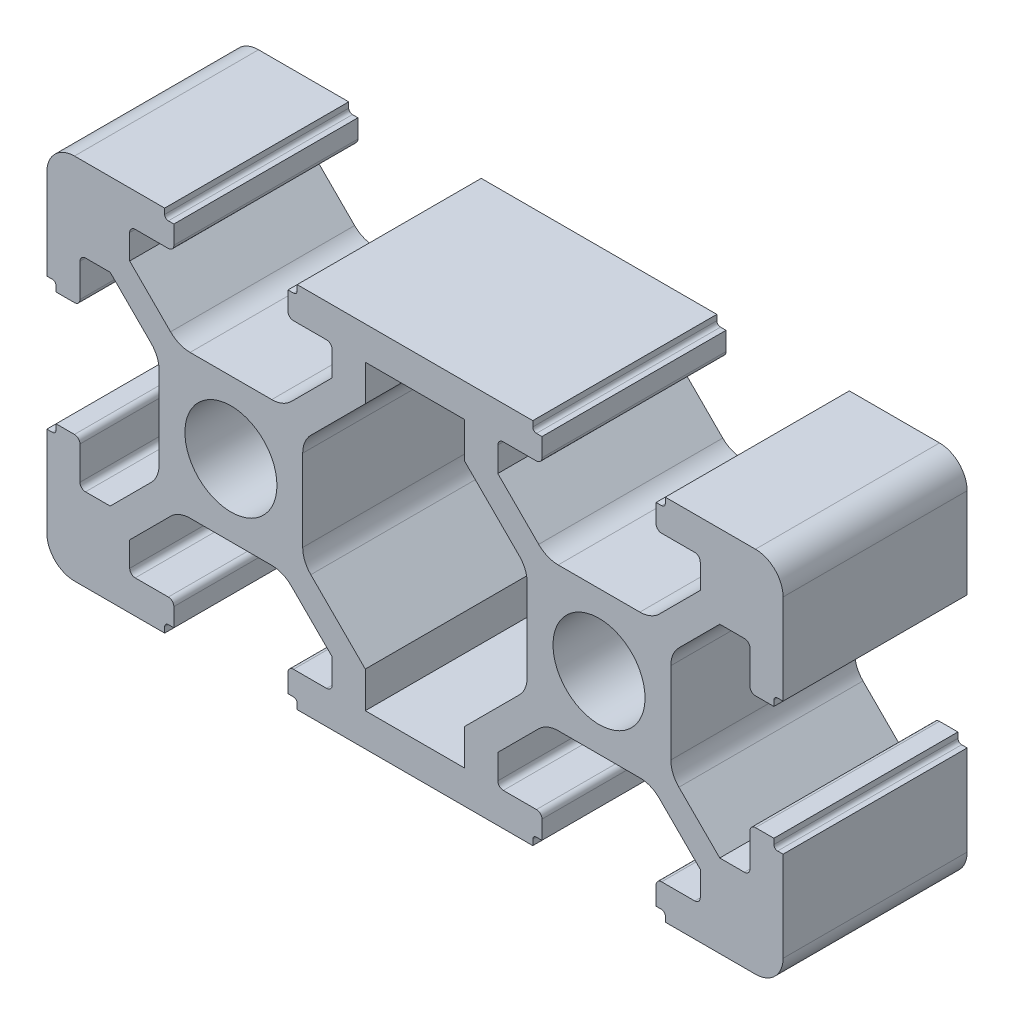
SolidWorks part; units mm, degrees
ref_plane "前视基准面" through (0, 0, 0) normal (0, 0, 1) x (1, 0, 0)
ref_plane "上视基准面" through (0, 0, 0) normal (0, 1, 0) x (1, 0, 0)
ref_plane "右视基准面" through (0, 0, 0) normal (1, 0, 0) x (0, 0, -1)
sketch "草图1" plane through (0, 0, 0) normal (0, 0, 1) x (1, 0, 0)
  line L0 (-1.9716, -6.6942) -> (-4.9322, -3.7335)
  line L1 (-5.3716, -2.6729) -> (-5.3716, 1.7645)
  line L2 (-4.9322, 2.8251) -> (-1.9716, 5.7858)
  line L3 (-0.7716, 9.5458) -> (-5.6716, 9.5458)
  line L4 (-5.6716, 9.5458) -> (-5.6716, 9.2458)
  line L5 (-5.8716, 9.0458) -> (-6.1716, 9.0458)
  line L6 (-6.1716, 9.0458) -> (-6.1716, 8.0458)
  line L7 (-5.8716, 7.7458) -> (-4.0716, 7.7458)
  line L8 (-3.7716, 7.4458) -> (-3.7716, 6.1058)
  line L9 (-3.7716, 6.1058) -> (-5.9922, 3.8851)
  line L10 (-7.0529, 3.4458) -> (-11.4903, 3.4458)
  line L11 (-12.5509, 3.8851) -> (-14.7716, 6.1058)
  line L12 (-14.7716, 6.1058) -> (-14.7716, 7.4458)
  line L13 (-14.4716, 7.7458) -> (-12.6716, 7.7458)
  line L14 (-12.3716, 8.0458) -> (-12.3716, 9.0458)
  line L15 (-12.3716, 9.0458) -> (-12.6716, 9.0458)
  line L16 (-12.8716, 9.2458) -> (-12.8716, 9.5458)
  line L17 (-12.8716, 9.5458) -> (-17.7716, 9.5458)
  line L18 (-19.2716, 8.0458) -> (-19.2716, 3.1458)
  line L19 (-19.2716, 3.1458) -> (-18.9716, 3.1458)
  line L20 (-18.7716, 2.9458) -> (-18.7716, 2.6458)
  line L21 (-18.7716, 2.6458) -> (-17.7716, 2.6458)
  line L22 (-17.4716, 2.9458) -> (-17.4716, 4.7458)
  line L23 (-17.1716, 5.0458) -> (-15.8316, 5.0458)
  line L24 (-15.8316, 5.0458) -> (-13.6109, 2.8251)
  line L25 (-13.1716, 1.7645) -> (-13.1716, -2.6729)
  line L26 (-13.6109, -3.7335) -> (-15.8316, -5.9542)
  line L27 (-15.8316, -5.9542) -> (-17.1716, -5.9542)
  line L28 (-17.4716, -5.6542) -> (-17.4716, -3.8542)
  line L29 (-17.7716, -3.5542) -> (-18.7716, -3.5542)
  line L30 (-18.7716, -3.5542) -> (-18.7716, -3.8542)
  line L31 (-18.9716, -4.0542) -> (-19.2716, -4.0542)
  line L32 (-19.2716, -4.0542) -> (-19.2716, -8.9542)
  line L33 (-17.7716, -10.4542) -> (-12.8716, -10.4542)
  line L34 (-12.8716, -10.4542) -> (-12.8716, -10.1542)
  line L35 (-12.6716, -9.9542) -> (-12.3716, -9.9542)
  line L36 (-12.3716, -9.9542) -> (-12.3716, -8.9542)
  line L37 (-12.6716, -8.6542) -> (-14.4716, -8.6542)
  line L38 (-14.7716, -8.3542) -> (-14.7716, -7.0142)
  line L39 (-14.7716, -7.0142) -> (-12.5509, -4.7935)
  line L40 (-11.4903, -4.3542) -> (-7.0529, -4.3542)
  line L41 (-5.9922, -4.7935) -> (-3.7716, -7.0142)
  line L42 (-3.7716, -7.0142) -> (-3.7716, -8.3542)
  line L43 (-4.0716, -8.6542) -> (-5.8716, -8.6542)
  line L44 (-6.1716, -8.9542) -> (-6.1716, -9.9542)
  line L45 (-6.1716, -9.9542) -> (-5.8716, -9.9542)
  line L46 (-5.6716, -10.1542) -> (-5.6716, -10.4542)
  line L47 (-5.6716, -10.4542) -> (-0.7716, -10.4542)
  line L48 (-0.7716, -10.4542) -> (7.1284, -10.4542)
  line L49 (7.1284, -10.4542) -> (7.1284, -10.1542)
  line L50 (7.3284, -9.9542) -> (7.6284, -9.9542)
  line L51 (7.6284, -9.9542) -> (7.6284, -8.9542)
  line L52 (7.3284, -8.6542) -> (5.5284, -8.6542)
  line L53 (5.2284, -8.3542) -> (5.2284, -7.0142)
  line L54 (5.2284, -7.0142) -> (7.4491, -4.7935)
  line L55 (8.5097, -4.3542) -> (12.9471, -4.3542)
  line L56 (14.0078, -4.7935) -> (16.2284, -7.0142)
  line L57 (16.2284, -7.0142) -> (16.2284, -8.3542)
  line L58 (15.9284, -8.6542) -> (14.1284, -8.6542)
  line L59 (13.8284, -8.9542) -> (13.8284, -9.9542)
  line L60 (13.8284, -9.9542) -> (14.1284, -9.9542)
  line L61 (14.3284, -10.1542) -> (14.3284, -10.4542)
  line L62 (14.3284, -10.4542) -> (19.2284, -10.4542)
  line L63 (20.7284, -8.9542) -> (20.7284, -4.0542)
  line L64 (20.7284, -4.0542) -> (20.4284, -4.0542)
  line L65 (20.2284, -3.8542) -> (20.2284, -3.5542)
  line L66 (20.2284, -3.5542) -> (19.2284, -3.5542)
  line L67 (18.9284, -3.8542) -> (18.9284, -5.6542)
  line L68 (18.6284, -5.9542) -> (17.2884, -5.9542)
  line L69 (17.2884, -5.9542) -> (15.0678, -3.7335)
  line L70 (14.6284, -2.6729) -> (14.6284, 1.7645)
  line L71 (15.0678, 2.8251) -> (17.2884, 5.0458)
  line L72 (17.2884, 5.0458) -> (18.6284, 5.0458)
  line L73 (18.9284, 4.7458) -> (18.9284, 2.9458)
  line L74 (19.2284, 2.6458) -> (20.2284, 2.6458)
  line L75 (20.2284, 2.6458) -> (20.2284, 2.9458)
  line L76 (20.4284, 3.1458) -> (20.7284, 3.1458)
  line L77 (20.7284, 3.1458) -> (20.7284, 8.0458)
  line L78 (19.2284, 9.5458) -> (14.3284, 9.5458)
  line L79 (14.3284, 9.5458) -> (14.3284, 9.2458)
  line L80 (14.1284, 9.0458) -> (13.8284, 9.0458)
  line L81 (13.8284, 9.0458) -> (13.8284, 8.0458)
  line L82 (14.1284, 7.7458) -> (15.9284, 7.7458)
  line L83 (16.2284, 7.4458) -> (16.2284, 6.1058)
  line L84 (16.2284, 6.1058) -> (14.0078, 3.8851)
  line L85 (12.9471, 3.4458) -> (8.5097, 3.4458)
  line L86 (7.4491, 3.8851) -> (5.2284, 6.1058)
  line L87 (5.2284, 6.1058) -> (5.2284, 7.4458)
  line L88 (5.5284, 7.7458) -> (7.3284, 7.7458)
  line L89 (7.6284, 8.0458) -> (7.6284, 9.0458)
  line L90 (7.6284, 9.0458) -> (7.3284, 9.0458)
  line L91 (7.1284, 9.2458) -> (7.1284, 9.5458)
  line L92 (7.1284, 9.5458) -> (2.2284, 9.5458)
  line L93 (3.4284, 5.7858) -> (6.3891, 2.8251)
  line L94 (6.8284, 1.7645) -> (6.8284, -2.6729)
  line L95 (6.3891, -3.7335) -> (3.4284, -6.6942)
  line L96 (-0.7716, 9.5458) -> (2.2284, 9.5458)
  line L99 (-1.9716, 7.7458) -> (3.4284, 7.7458)
  line L100 (3.4284, 7.7458) -> (3.4284, 5.7858)
  line L101 (-1.9716, 7.7458) -> (-1.9716, 5.7858)
  line L102 (-1.9716, -8.6542) -> (3.4284, -8.6542)
  line L103 (3.4284, -8.6542) -> (3.4284, -6.6942)
  line L104 (-1.9716, -8.6542) -> (-1.9716, -6.6942)
  arc A1 (-5.3716, -2.6729) -> (-4.9322, -3.7335) centre (-3.8716, -2.6729) ccw
  arc A2 (-4.9322, 2.8251) -> (-5.3716, 1.7645) centre (-3.8716, 1.7645) ccw
  arc A3 (-5.8716, 9.0458) -> (-5.6716, 9.2458) centre (-5.8716, 9.2458) ccw
  arc A4 (-6.1716, 8.0458) -> (-5.8716, 7.7458) centre (-5.8716, 8.0458) ccw
  arc A5 (-3.7716, 7.4458) -> (-4.0716, 7.7458) centre (-4.0716, 7.4458) ccw
  arc A6 (-7.0529, 3.4458) -> (-5.9922, 3.8851) centre (-7.0529, 4.9458) ccw
  arc A7 (-12.5509, 3.8851) -> (-11.4903, 3.4458) centre (-11.4903, 4.9458) ccw
  arc A8 (-14.4716, 7.7458) -> (-14.7716, 7.4458) centre (-14.4716, 7.4458) ccw
  arc A9 (-12.6716, 7.7458) -> (-12.3716, 8.0458) centre (-12.6716, 8.0458) ccw
  arc A10 (-12.8716, 9.2458) -> (-12.6716, 9.0458) centre (-12.6716, 9.2458) ccw
  arc A11 (-17.7716, 9.5458) -> (-19.2716, 8.0458) centre (-17.7716, 8.0458) ccw
  arc A12 (-18.7716, 2.9458) -> (-18.9716, 3.1458) centre (-18.9716, 2.9458) ccw
  arc A13 (-17.7716, 2.6458) -> (-17.4716, 2.9458) centre (-17.7716, 2.9458) ccw
  arc A14 (-17.1716, 5.0458) -> (-17.4716, 4.7458) centre (-17.1716, 4.7458) ccw
  arc A15 (-13.1716, 1.7645) -> (-13.6109, 2.8251) centre (-14.6716, 1.7645) ccw
  arc A16 (-13.6109, -3.7335) -> (-13.1716, -2.6729) centre (-14.6716, -2.6729) ccw
  arc A17 (-17.4716, -5.6542) -> (-17.1716, -5.9542) centre (-17.1716, -5.6542) ccw
  arc A18 (-17.4716, -3.8542) -> (-17.7716, -3.5542) centre (-17.7716, -3.8542) ccw
  arc A19 (-18.9716, -4.0542) -> (-18.7716, -3.8542) centre (-18.9716, -3.8542) ccw
  arc A20 (-19.2716, -8.9542) -> (-17.7716, -10.4542) centre (-17.7716, -8.9542) ccw
  arc A21 (-12.6716, -9.9542) -> (-12.8716, -10.1542) centre (-12.6716, -10.1542) ccw
  arc A22 (-12.3716, -8.9542) -> (-12.6716, -8.6542) centre (-12.6716, -8.9542) ccw
  arc A23 (-14.7716, -8.3542) -> (-14.4716, -8.6542) centre (-14.4716, -8.3542) ccw
  arc A24 (-11.4903, -4.3542) -> (-12.5509, -4.7935) centre (-11.4903, -5.8542) ccw
  arc A25 (-5.9922, -4.7935) -> (-7.0529, -4.3542) centre (-7.0529, -5.8542) ccw
  arc A26 (-4.0716, -8.6542) -> (-3.7716, -8.3542) centre (-4.0716, -8.3542) ccw
  arc A27 (-5.8716, -8.6542) -> (-6.1716, -8.9542) centre (-5.8716, -8.9542) ccw
  arc A28 (-5.6716, -10.1542) -> (-5.8716, -9.9542) centre (-5.8716, -10.1542) ccw
  arc A29 (7.3284, -9.9542) -> (7.1284, -10.1542) centre (7.3284, -10.1542) ccw
  arc A30 (7.6284, -8.9542) -> (7.3284, -8.6542) centre (7.3284, -8.9542) ccw
  arc A31 (5.2284, -8.3542) -> (5.5284, -8.6542) centre (5.5284, -8.3542) ccw
  arc A32 (8.5097, -4.3542) -> (7.4491, -4.7935) centre (8.5097, -5.8542) ccw
  arc A33 (14.0078, -4.7935) -> (12.9471, -4.3542) centre (12.9471, -5.8542) ccw
  arc A34 (15.9284, -8.6542) -> (16.2284, -8.3542) centre (15.9284, -8.3542) ccw
  arc A35 (14.1284, -8.6542) -> (13.8284, -8.9542) centre (14.1284, -8.9542) ccw
  arc A36 (14.3284, -10.1542) -> (14.1284, -9.9542) centre (14.1284, -10.1542) ccw
  arc A37 (19.2284, -10.4542) -> (20.7284, -8.9542) centre (19.2284, -8.9542) ccw
  arc A38 (20.2284, -3.8542) -> (20.4284, -4.0542) centre (20.4284, -3.8542) ccw
  arc A39 (19.2284, -3.5542) -> (18.9284, -3.8542) centre (19.2284, -3.8542) ccw
  arc A40 (18.6284, -5.9542) -> (18.9284, -5.6542) centre (18.6284, -5.6542) ccw
  arc A41 (14.6284, -2.6729) -> (15.0678, -3.7335) centre (16.1284, -2.6729) ccw
  arc A42 (15.0678, 2.8251) -> (14.6284, 1.7645) centre (16.1284, 1.7645) ccw
  arc A43 (18.9284, 4.7458) -> (18.6284, 5.0458) centre (18.6284, 4.7458) ccw
  arc A44 (18.9284, 2.9458) -> (19.2284, 2.6458) centre (19.2284, 2.9458) ccw
  arc A45 (20.4284, 3.1458) -> (20.2284, 2.9458) centre (20.4284, 2.9458) ccw
  arc A46 (20.7284, 8.0458) -> (19.2284, 9.5458) centre (19.2284, 8.0458) ccw
  arc A47 (14.1284, 9.0458) -> (14.3284, 9.2458) centre (14.1284, 9.2458) ccw
  arc A48 (13.8284, 8.0458) -> (14.1284, 7.7458) centre (14.1284, 8.0458) ccw
  arc A49 (16.2284, 7.4458) -> (15.9284, 7.7458) centre (15.9284, 7.4458) ccw
  arc A50 (12.9471, 3.4458) -> (14.0078, 3.8851) centre (12.9471, 4.9458) ccw
  arc A51 (7.4491, 3.8851) -> (8.5097, 3.4458) centre (8.5097, 4.9458) ccw
  arc A52 (5.5284, 7.7458) -> (5.2284, 7.4458) centre (5.5284, 7.4458) ccw
  arc A53 (7.3284, 7.7458) -> (7.6284, 8.0458) centre (7.3284, 8.0458) ccw
  arc A54 (7.1284, 9.2458) -> (7.3284, 9.0458) centre (7.3284, 9.2458) ccw
  arc A55 (6.8284, 1.7645) -> (6.3891, 2.8251) centre (5.3284, 1.7645) ccw
  arc A56 (6.3891, -3.7335) -> (6.8284, -2.6729) centre (5.3284, -2.6729) ccw
  circle A58 centre (10.7284, -0.4542) radius 2.5
  circle A63 centre (-9.2716, -0.4542) radius 2.5
extrude "凸台-拉伸1" add sketch "草图1" along normal blind 10
